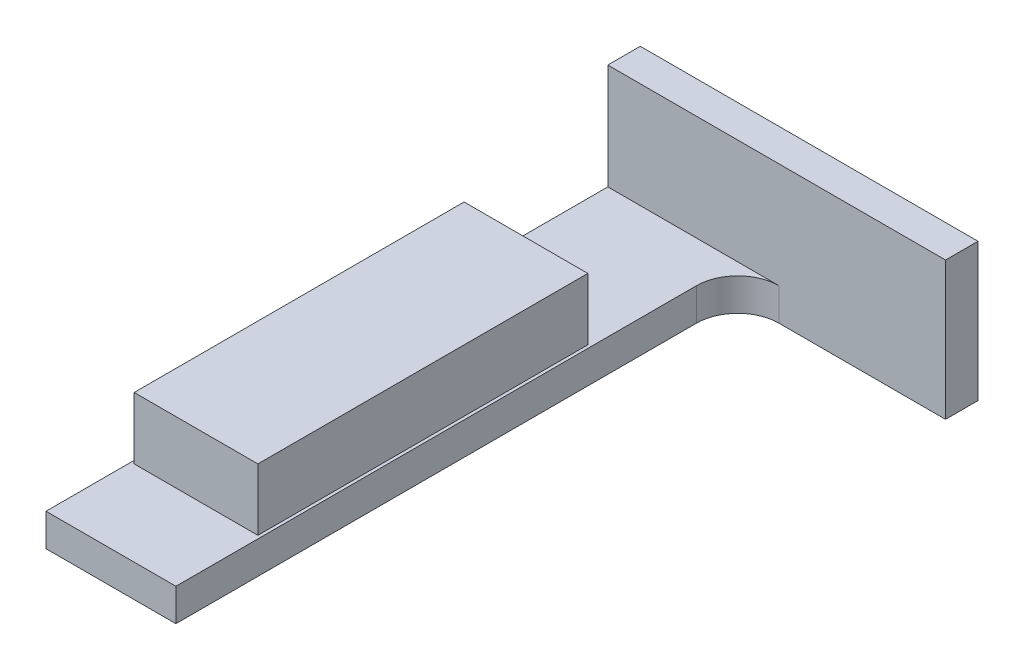
SolidWorks part; units mm, degrees
material "Aluminum Black Anodize"
ref_plane "Front" through (0, 0, 0) normal (0, 0, 1) x (1, 0, 0)
ref_plane "Top" through (0, 0, 0) normal (0, 1, 0) x (1, 0, 0)
ref_plane "Right" through (0, 0, 0) normal (1, 0, 0) x (0, 0, -1)
sketch "Sketch1" plane through (0, 0, 0) normal (0, 0, 1) x (1, 0, 0)
  line L1 (0, 0) -> (52, 0)
  line L2 (0, 0) -> (0, -21.25)
  line L3 (0, -21.25) -> (52, -21.25)
  line L4 (52, 0) -> (52, -21.25)
  dimension "D1" = 52
  dimension "D2" = 21.25
extrude "Extrude1" add sketch "Sketch1" along normal blind 5
sketch "Sketch2" plane through (0, 0, 5) normal (0, 0, 1) x (1, 0, 0)
  line L0 (0, -21.25) -> (52, -21.25) construction
  line L1 (0, -21.25) -> (20, -21.25)
  line L2 (0, -21.25) -> (0, -16.25)
  line L3 (0, -16.25) -> (20, -16.25)
  line L4 (20, -21.25) -> (20, -16.25)
  dimension "D1" = 5
  dimension "D2" = 20
extrude "Extrude2" add sketch "Sketch2" along normal blind 86.5
fillet "Fillet1" radius 6.35 1 edges
sketch "Sketch3" plane through (0, -16.25, 0) normal (0, 1, 0) x (1, 0, 0)
  line L0 (10, -91.5) -> (10, -78.4) construction
  line L1 (0.475, -27.6) -> (19.525, -27.6)
  line L2 (0.475, -27.6) -> (0.475, -78.4)
  line L3 (0.475, -78.4) -> (19.525, -78.4)
  line L4 (19.525, -27.6) -> (19.525, -78.4)
  line L5 (20, -91.5) -> (0, -91.5) construction
  line L6 (26.35, -5) -> (0, -5) construction
  dimension "D1" = 50.8
  dimension "D2" = 19.05
  dimension "D3" = 22.6
extrude "Extrude3" add sketch "Sketch3" along normal blind 9.525
